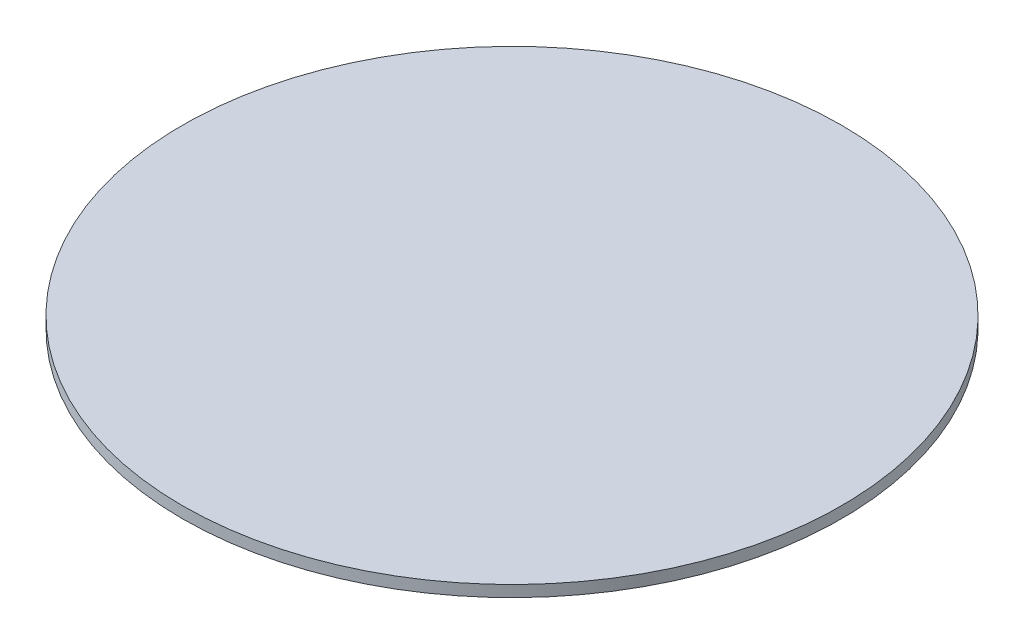
SolidWorks part; units mm, degrees
ref_plane "Front Plane" through (0, 0, 0) normal (0, 0, 1) x (1, 0, 0)
ref_plane "Top Plane" through (0, 0, 0) normal (0, 1, 0) x (1, 0, 0)
ref_plane "Right Plane" through (0, 0, 0) normal (1, 0, 0) x (0, 0, -1)
sketch "Sketch1" plane through (0, 0, 0) normal (0, 1, 0) x (1, 0, 0)
  circle A0 centre (0, 0) radius 92.075
  dimension "D1" = 184.15
extrude "Boss-Extrude1" add sketch "Sketch1" along normal blind 3.175
ref_plane "Plane1" through (0, 0, 0) normal (0, 0, 1) x (1, 0, 0)
